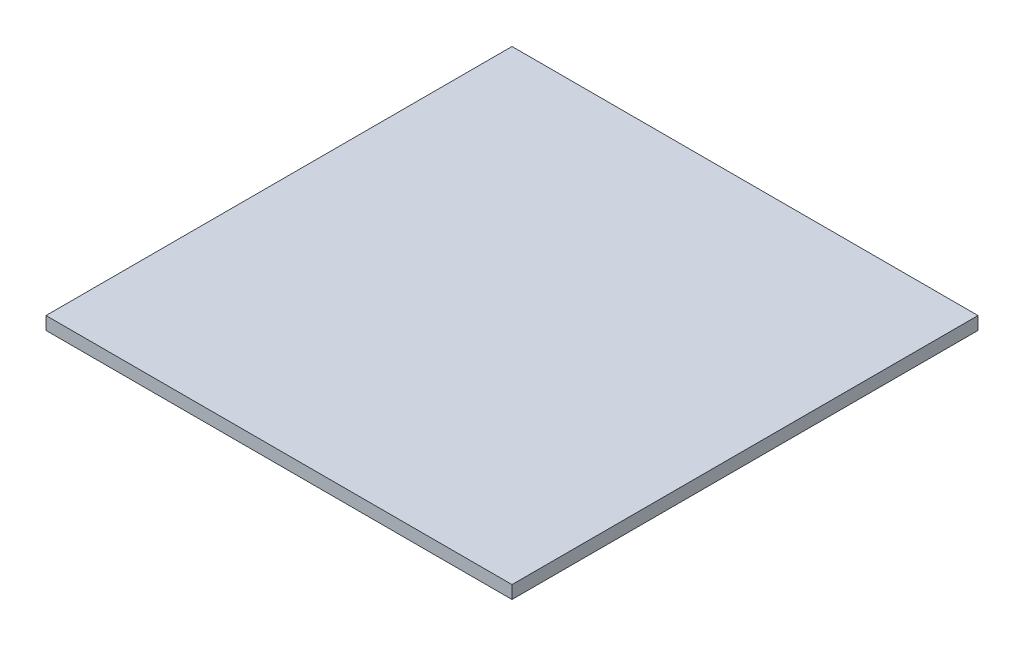
SolidWorks part; units mm, degrees
ref_plane "Front Plane" through (0, 0, 0) normal (0, 0, 1) x (1, 0, 0)
ref_plane "Top Plane" through (0, 0, 0) normal (0, 1, 0) x (1, 0, 0)
ref_plane "Right Plane" through (0, 0, 0) normal (1, 0, 0) x (0, 0, -1)
sketch "Sketch2" plane through (0, 0, 0) normal (0, 1, 0) x (1, 0, 0)
  line L1 (-914.4, -914.4) -> (914.4, -914.4)
  line L2 (-914.4, -914.4) -> (-914.4, 914.4)
  line L3 (-914.4, 914.4) -> (914.4, 914.4)
  line L4 (914.4, -914.4) -> (914.4, 914.4)
  line L5 (-914.4, -914.4) -> (914.4, 914.4) construction
  line L6 (-914.4, 914.4) -> (914.4, -914.4) construction
  point P0 (0, 0)
  dimension "D1" = 1828.8
  dimension "D2" = 1828.8
extrude "Boss-Extrude1" add sketch "Sketch2" along normal blind 50.8
